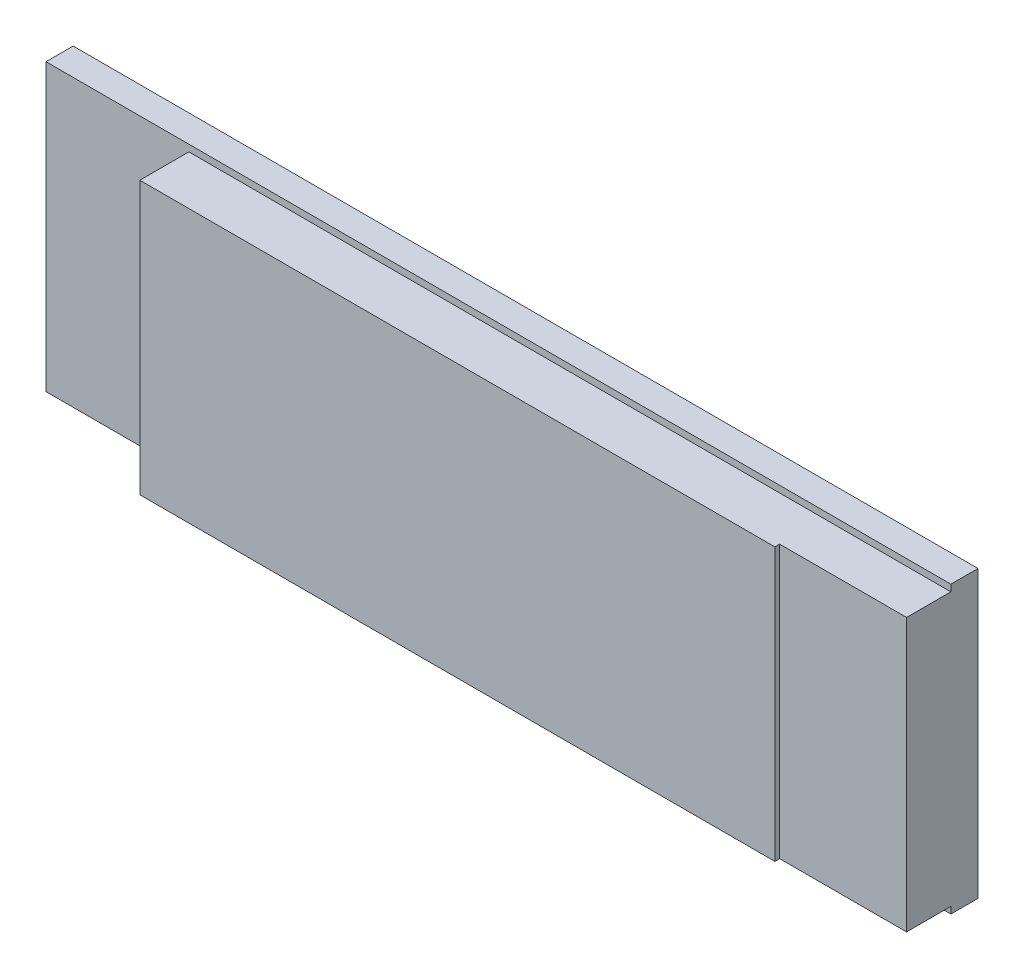
SolidWorks part; units mm, degrees
ref_plane "Спереди" through (0, 0, 0) normal (0, 0, 1) x (1, 0, 0)
ref_plane "Сверху" through (0, 0, 0) normal (0, 1, 0) x (1, 0, 0)
ref_plane "Справа" through (0, 0, 0) normal (1, 0, 0) x (0, 0, -1)
sketch "Эскиз1" plane through (0, 0, 0) normal (0, 0, 1) x (1, 0, 0)
  line L1 (-19, -6) -> (19, -6)
  line L2 (-19, -6) -> (-19, 6)
  line L3 (-19, 6) -> (19, 6)
  line L4 (19, -6) -> (19, 6)
  line L5 (-19, -6) -> (19, 6) construction
  line L6 (-19, 6) -> (19, -6) construction
  point P0 (0, 0)
  dimension "D1" = 38
  dimension "D2" = 12
extrude "Бобышка-Вытянуть1" add sketch "Эскиз1" along normal blind 1.14
sketch "Эскиз2" plane through (0, 0, 0) normal (0, 0, -1) x (-1, 0, 0)
  line L0 (19, -6) -> (-19, -6) construction
  line L1 (9.78, -2.72) -> (8.48, -2.72)
  line L2 (9.78, -2.72) -> (9.78, 0.12)
  line L3 (9.78, 0.12) -> (8.48, 0.12)
  line L4 (8.48, -2.72) -> (8.48, 0.12)
  line L5 (9.78, -2.72) -> (8.48, 0.12) construction
  line L6 (9.78, 0.12) -> (8.48, -2.72) construction
  line L7 (19, 6) -> (19, -6) construction
  point P0 (9.13, -1.3)
  dimension "D1" = 4.7
  dimension "D2" = 9.87
  dimension "D3" = 1.3
  dimension "D4" = 2.84
extrude "Бобышка-Вытянуть2" add sketch "Эскиз2" along normal blind 1.17
sketch "Эскиз3" plane through (0, 0, 1.14) normal (0, 0, 1) x (1, 0, 0)
  line L0 (19, -6) -> (19, 6) construction
  line L1 (-13, 5.72) -> (19, 5.72)
  line L2 (-13, 5.72) -> (-13, -5.72)
  line L3 (-13, -5.72) -> (19, -5.72)
  line L4 (19, 5.72) -> (19, -5.72)
  line L5 (-19, 6) -> (-19, -6) construction
  point P0 (0, 0)
  dimension "D1" = 11.44
  dimension "D2" = 6
extrude "Бобышка-Вытянуть3" add sketch "Эскиз3" along direction (0, 0, -1) on the side of the normal blind 1.86
sketch "Эскиз4" plane through (0, 0, 3) normal (0, 0, 1) x (1, 0, 0)
  line L0 (-13, -5.72) -> (19, -5.72) construction
  line L1 (-13, 5.72) -> (13.67, 5.72)
  line L2 (-13, 5.72) -> (-13, -5.72)
  line L3 (-13, -5.72) -> (13.67, -5.72)
  line L4 (13.67, 5.72) -> (13.67, -5.72)
  dimension "D1" = 26.67
extrude "Бобышка-Вытянуть4" add sketch "Эскиз4" along normal blind 0.2
